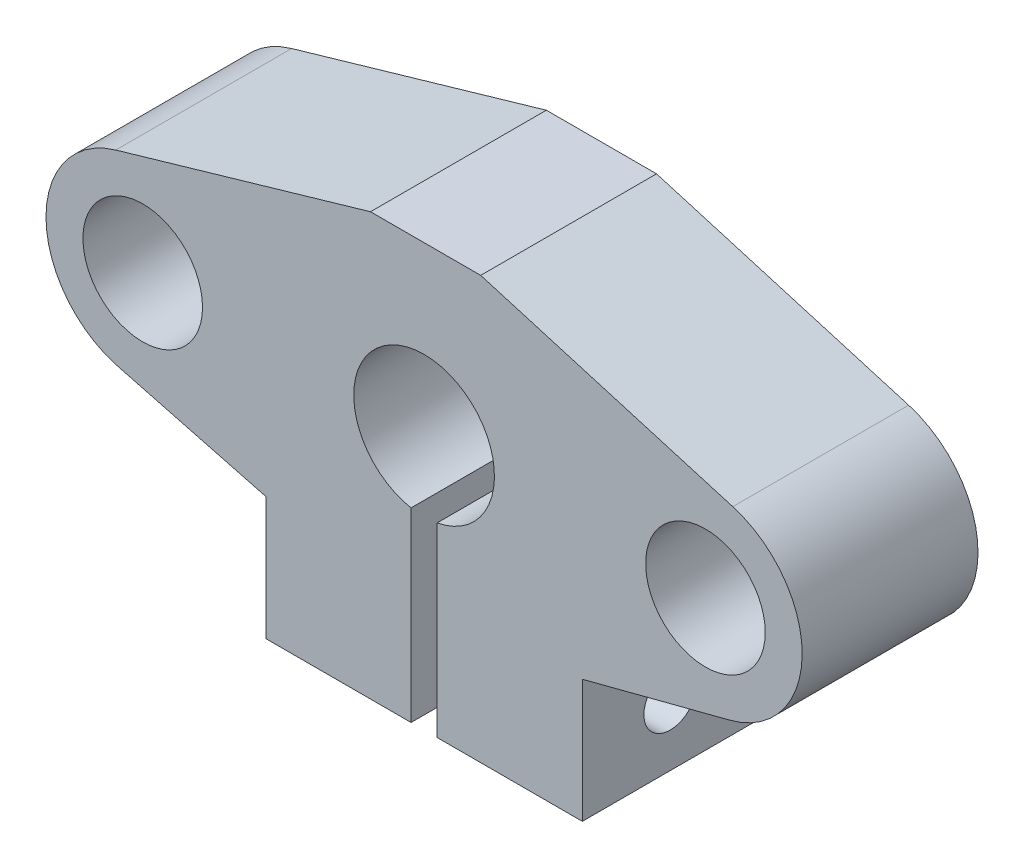
SolidWorks part; units mm, degrees
material "AISI 304"
ref_plane "Front Plane" through (0, 0, 0) normal (0, 0, 1) x (1, 0, 0)
ref_plane "Top Plane" through (0, 0, 0) normal (0, 1, 0) x (1, 0, 0)
ref_plane "Right Plane" through (0, 0, 0) normal (1, 0, 0) x (0, 0, -1)
sketch "Sketch2" plane through (0, 0, 0) normal (0, 0, 1) x (1, 0, 0)
  line L0 (-3.0468, 9.5) -> (3.2196, 9.5)
  line L1 (-3.0468, 9.5) -> (-17.533, 5.2955)
  line L2 (3.2196, 9.5) -> (17.5547, 5.2753)
  line L4 (0.7404, -14.5) -> (9, -14.5)
  line L5 (-9, -7.5) -> (-17.5974, -5.2494)
  line L6 (9, -7.5) -> (17.3824, -5.323)
  line L8 (-9, -7.5) -> (-9, -14.5)
  line L9 (-9, -14.5) -> (-0.7404, -14.5)
  line L10 (9, -7.5) -> (9, -14.5)
  line L12 (-0.7404, -14.5) -> (-0.7404, -3.9309)
  line L14 (0.7404, -14.5) -> (0.7404, -3.9309)
  arc A0 (0.7404, -3.9309) -> (-0.7404, -3.9309) centre (0, 0) ccw
  circle A1 centre (-16, 0.0135) radius 3.4
  circle A2 centre (16, 0) radius 3.4
  arc A3 (-17.533, 5.2955) -> (-17.5974, -5.2494) centre (-16, 0.0135) ccw
  arc A4 (17.3824, -5.323) -> (17.5547, 5.2753) centre (16, 0) ccw
  point P10 (0.0864, 9.5)
  point P20 (0, -14.5)
  dimension "D1" = 6.8
  dimension "D2" = 11
  dimension "D3" = 8
  dimension "D6" = 9.5
  dimension "D7" = 3.1332
  dimension "D4" = 16
  dimension "D5" = 16
  dimension "D9" = 18
  dimension "D10" = 7
extrude "Boss-Extrude2" add sketch "Sketch2" along normal blind 10
sketch "Sketch3" plane through (-9, 0, 0) normal (-1, 0, 0) x (0, 0, 1)
  line L0 (0, -7.5) -> (0, -14.5) construction
  line L1 (10, -14.5) -> (0, -14.5) construction
  circle A0 centre (5, -11) radius 1.5
  dimension "D3" = 3
  dimension "D1" = 5
  dimension "D2" = 3.5
extrude "Cut-Extrude1" cut sketch "Sketch3" against normal blind 30
